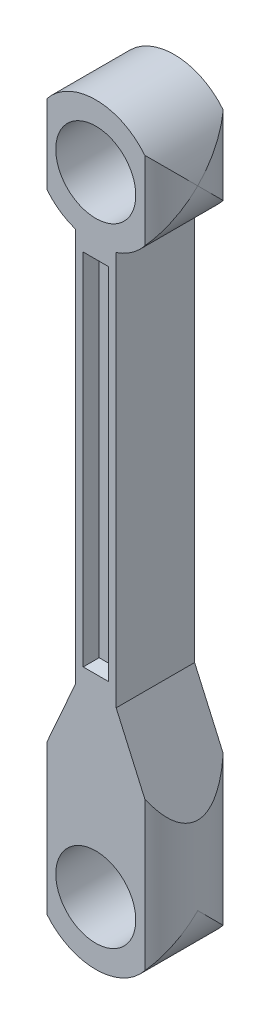
SolidWorks part; units mm, degrees
ref_plane "Front Plane" through (0, 0, 0) normal (0, 0, 1) x (1, 0, 0)
ref_plane "Top Plane" through (0, 0, 0) normal (0, 1, 0) x (1, 0, 0)
ref_plane "Right Plane" through (0, 0, 0) normal (1, 0, 0) x (0, 0, -1)
sketch "Sketch1" plane through (0, 0, 0) normal (0, 0, 1) x (1, 0, 0)
  line L0 (10.16, 12.7) -> (10.16, 50012.7) construction
  line L1 (-10.16, 12.7) -> (-10.16, 50012.7) construction
  line L2 (-10.16, 0) -> (-10.16, 12.7)
  line L3 (0, 0) -> (0, 50000) construction
  line L4 (10.16, 0) -> (10.16, 12.7)
  line L5 (-10.16, 12.7) -> (-3.302, 28.176)
  line L6 (10.16, 12.7) -> (3.302, 28.176)
  line L7 (-3.302, 91.9915) -> (-3.302, 28.176)
  line L8 (3.302, 91.9915) -> (3.302, 28.176)
  arc A0 (-10.16, 0) -> (10.16, 0) centre (0, 0) ccw
  circle A1 centre (0, 0) radius 6.477
  arc A2 (3.302, 91.9915) -> (-3.302, 91.9915) centre (0, 101.6) ccw
  circle A3 centre (0, 101.6) radius 6.477
  point P19 (0, 0)
  point P20 (0, 0)
  point P22 (0, 0)
  point P23 (0, 0)
  point P24 (-3.302, 91.9915)
  dimension "D1" = 20.32
  dimension "D4" = 12.954
  dimension "D9" = 20.32
  dimension "D11" = 12.954
  dimension "D2" = 20.32
  dimension "D3" = 12.7
  dimension "D5" = 23.9
  dimension "D6" = 23.9
  dimension "D7" = 3.302
  dimension "D8" = 3.302
  dimension "D10" = 101.6
extrude "Boss-Extrude1" add sketch "Sketch1" along normal blind 12.7
sketch "Sketch2" plane through (0, 0, 12.7) normal (0, 0, 1) x (1, 0, 0)
  line L0 (3.302, 28.176) -> (3.302, 91.9915) construction
  line L1 (-2.032, 89.408) -> (2.032, 89.408)
  line L2 (-2.032, 89.408) -> (-2.032, 31.242)
  line L3 (-2.032, 31.242) -> (2.032, 31.242)
  line L4 (2.032, 89.408) -> (2.032, 31.242)
  line L5 (-3.302, 91.9915) -> (-3.302, 28.176) construction
  point P4 (0, 89.408)
  point P7 (0, 31.242)
  dimension "D1" = 12.192
  dimension "D2" = 31.242
  dimension "D3" = 1.27
  dimension "D4" = 1.27
extrude "Cut-Extrude1" cut sketch "Sketch2" against normal blind 2.032 draft 15
sketch "Sketch3" plane through (0, 0, 0) normal (0, 0, -1) x (-1, 0, 0)
  line L0 (-3.302, 28.176) -> (-3.302, 91.9915) construction
  line L1 (-2.032, 89.408) -> (2.032, 89.408)
  line L2 (-2.032, 89.408) -> (-2.032, 31.242)
  line L3 (-2.032, 31.242) -> (2.032, 31.242)
  line L4 (2.032, 89.408) -> (2.032, 31.242)
  line L5 (3.302, 91.9915) -> (3.302, 28.176) construction
  dimension "D1" = 12.192
  dimension "D2" = 31.242
  dimension "D3" = 1.27
  dimension "D4" = 1.27
extrude "Cut-Extrude2" cut sketch "Sketch3" against normal blind 2.032 draft 15
sketch "Sketch4" plane through (0, 0, 0) normal (0, 1, 0) x (1, 0, 0)
  line L0 (0, -12.7) -> (0, 0) construction
  line L1 (6.477, 0) -> (-6.477, 0) construction
  circle A0 centre (0, -6.35) radius 10.16
  dimension "D2" = 20.32
  dimension "D1" = 6.35
extrude "Cut-Extrude3" cut sketch "Sketch4" against normal blind 10.16 and the other way through all flip side to cut
